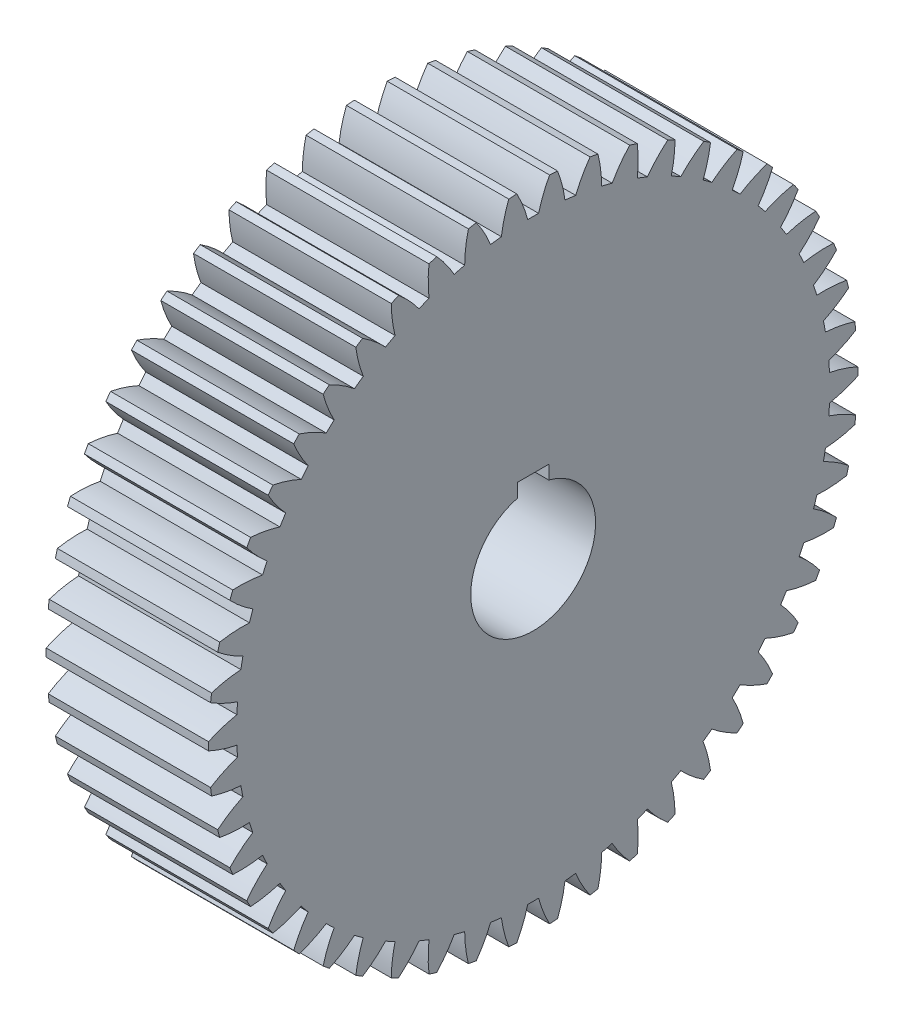
SolidWorks part; units mm, degrees
ref_plane "Plane1" through (0, 0, 0) normal (0, 0, 1) x (1, 0, 0)
ref_plane "Plane2" through (0, 0, 0) normal (0, 1, 0) x (1, 0, 0)
ref_plane "Plane3" through (0, 0, 0) normal (1, 0, 0) x (0, 0, -1)
sketch "HoldingSke" plane through (0, 0, 0) normal (0, 1, 0) x (1, 0, 0)
  line L0 (0, 0) -> (130.6144, -155.6602)
  line L1 (-15, 0) -> (100, 0) construction
  line L2 (0, 0) -> (-2.1039, 2.3779)
  line L3 (0, 0) -> (-11.863, 4.5341)
  line L4 (0, 0) -> (5.5511, 6.6156)
  line L5 (0, 0) -> (-47.5972, -17.7524)
  line L6 (0, 0) -> (-34.2154, -23.0853)
  line L7 (-2.1039, 2.3779) -> (8.8308, 51.9871)
  line L8 (-76.2, 54.61) -> (-41.4782, 54.61)
  line L9 (-71.009, 38.7566) -> (-53.1078, 45.2721)
  line L10 (-76.2, 71.12) -> (104.1128, 71.12)
  line L11 (0, 0) -> (-41.275, 0)
  line L12 (-76.2, 101.6) -> (-76.0857, 101.6)
  line L13 (24.9733, 27.94) -> (52.9518, 28.4284)
  line L14 (24.9733, 27.94) -> (24.9746, 27.94)
  line L15 (24.9733, 27.94) -> (100.4006, 29.5858)
  circle A0 centre (0, 0) radius 15.875
  circle A1 centre (0, 0) radius 38.1
  circle A2 centre (0, 0) radius 38.1
  circle A3 centre (0, 0) radius 15.875
  dimension "MHD" = 76.2
  dimension "Hub_dia" = 76.2
  dimension "Bore" = 31.75
  dimension "MBD" = 31.75
  dimension "Num_teeth" = 50
  dimension "Pitch" = 203.2
  dimension "Overall_len" = 50.8
  dimension "Show_teeth" = 50
  dimension "Thickness" = 41.275
  dimension "OAL" = 50.8001
  dimension "T_dim" = 34.7218
  dimension "Ap" = 20
  dimension "H" = 19.05
  dimension "Pitch_radius" = 180.3128
  dimension "Width" = 41.275
  dimension "Backlash" = 0.1143
  dimension "Addendum_fac" = 1
  dimension "Dedendum_fac" = 1.25
  dimension "Clearance_fac" = 0.25
  dimension "Dedendum_add" = 0.0013
sketch "BasProSke" plane through (0, 0, 0) normal (0, 1, 0) x (1, 0, 0)
  line L0 (-10, 0) -> (60, 0) construction
  line L1 (0, 0) -> (0, 82.55)
  line L2 (0, 0) -> (41.275, 0)
  line L3 (41.275, 0) -> (41.275, 82.55)
  line L4 (41.275, 82.55) -> (0, 82.55)
  dimension "Thickness" = 41.275
  dimension "Diameter" = 165.1
revolve "Base-Revolve" add sketch "BasProSke" angle 360 about L0
sketch "TooCutSke" plane through (0, 0, 0) normal (1, 0, 0) x (0, 0, -1)
  line L1 (0, 0) -> (0, 107) construction
  line L2 (0, 0) -> (-2.6932, 79.3293) construction
  line L3 (0, 0) -> (-9.9638, 158.3706) construction
  line L4 (-2.6932, 79.3293) -> (-4.9819, 79.1853) construction
  arc A0 (1.3795, 75.3924) -> (-1.3795, 75.3924) centre (0, 0) ccw
  arc A1 (4.1801, 82.4695) -> (-4.1801, 82.4695) centre (0, 0) ccw
  circle A2 centre (0, 0) radius 79.375 construction
  circle A3 centre (0, 0) radius 74.5881 construction
  arc A4 (-1.3795, 75.3924) -> (-4.1801, 82.4695) centre (-32.0894, 67.3324) ccw
  arc A5 (4.1801, 82.4695) -> (1.3795, 75.3924) centre (32.0894, 67.3324) ccw
  dimension "Root_dia" = 150.81
  dimension "Overcut_dia" = 165.1508
  dimension "Pitch_dia" = 158.75
  dimension "Base_dia" = 149.1762
  dimension "Flank_rad" = 31.75
  dimension "Half_ang" = 3.6
  dimension "Half_CT" = 2.2932
extrude "ToothCut" cut sketch "TooCutSke" along normal through all
fillet "Breaks" [suppressed] radius 0.0635
fillet "RootFillets" [suppressed] radius 0.795
pattern_circular "TeethCuts" count 50 every 7.2 about axis through (-10, 0, 0) along (1, 0, 0) of "ToothCut", "RootFillets", "Breaks"
sketch "HubNeaOneSke" plane through (0, 0, 0) normal (-1, 0, 0) x (0, 0, 1)
  circle A0 centre (0, 0) radius 38.1
  dimension "Diameter" = 76.2
extrude "HubNearOne" [suppressed] add sketch "HubNeaOneSke" along normal blind 9.5251
sketch "HubNeaBotSke" plane through (0, 0, 0) normal (-1, 0, 0) x (0, 0, 1)
  circle A0 centre (0, 0) radius 38.1
  dimension "Diameter" = 76.2
extrude "HubNearBoth" [suppressed] add sketch "HubNeaBotSke" along normal blind 4.7625
ref_plane "FarPln" through (41.275, 0, 0) normal (1, 0, 0) x (0, 0, -1)
sketch "HubFarSke" plane through (41.275, 0, 0) normal (1, 0, 0) x (0, 0, -1)
  circle A0 centre (0, 0) radius 38.1
  dimension "Diameter" = 76.2
extrude "HubFar" [suppressed] add sketch "HubFarSke" along normal blind 4.7625
sketch "BorSke" plane through (0, 0, 0) normal (1, 0, 0) x (0, 0, -1)
  circle A0 centre (0, 0) radius 15.875
  dimension "Diameter" = 31.75
extrude "Bore" cut sketch "BorSke" along normal mid plane 101.6001
sketch "KeySke" plane through (0, 0, 0) normal (1, 0, 0) x (0, 0, -1)
  line L0 (-3.9624, 0) -> (-3.9624, 18.8468)
  line L1 (-3.9624, 18.8468) -> (3.9624, 18.8468)
  line L2 (3.9624, 18.8468) -> (3.9624, 0)
  line L3 (0, 0) -> (0, 34) construction
  line L4 (-3.9624, 0) -> (3.9624, 0)
  dimension "Offset" = 18.8468
  dimension "Width" = 7.9248
extrude "Keyway" cut sketch "KeySke" along normal mid plane 101.6001
pattern_circular "Keyway2" [suppressed] count 2 every 90 about axis through (-10, 0, 0) along (1, 0, 0)
equation "' \"Pitch@HoldingSke\" = 4"
equation "' \"Num_teeth@HoldingSke\" = 12"
equation "' \"Ap@HoldingSke\" =  20"
equation "' \"Ap@HoldingSke\" = 20"
equation "' \"Width@HoldingSke\" = 0.5"
equation "' \"Hub_dia@HoldingSke\"= 1"
equation "' \"Hub_dia@HoldingSke\" = 1"
equation "' \"Overall_len@HoldingSke\" = 1.0"
equation "' \"Bore@HoldingSke\" = 0.75"
equation "' \"T_dim@HoldingSke\" = 0.85"
equation "' \"Width@KeySke\" = 0.25"
equation "' \"Show_teeth@HoldingSke\" = 13"
equation "' \"Backlash@HoldingSke\" = 0.009"
equation "' \"Addendum_fac@HoldingSke\" = 1.0"
equation "' \"Dedendum_fac@HoldingSke\" = 1.25"
equation "' \"Dedendum_add@HoldingSke\" = 0.00005"
equation "' \"Clearance_fac@HoldingSke\" = 0.25"
equation "' \"Pitch@HoldingSke\" = 0.5"
equation "' \"Num_teeth@HoldingSke\" = 23"
equation "' \"Show_teeth@HoldingSke\" = 23"
equation "' \"Backlash@HoldingSke\" = 0.0375"
equation "\"Overcut_dia@TooCutSke\" = (\"Num_teeth@HoldingSke\" + 2 * \"Addendum_fac@HoldingSke\") / \"Pitch@HoldingSke\" + 0.002"
equation "\"Pitch_dia@TooCutSke\" = \"Num_teeth@HoldingSke\" / \"Pitch@HoldingSke\""
equation "\"Base_dia@TooCutSke\" = \"Num_teeth@HoldingSke\" / \"Pitch@HoldingSke\" * cos((\"Ap@HoldingSke\"  * 3.14159265 / 180))"
equation "\"Root_dia@TooCutSke\" = (\"Num_teeth@HoldingSke\" + 2) / \"Pitch@HoldingSke\" - 2 * (\"Addendum_fac@HoldingSke\" + \"Dedendum_fac@HoldingSke\") / \"Pitch@HoldingSke\" - \"Dedendum_add@HoldingSke\" * 2"
equation "\"Half_ang@TooCutSke\" = 180 / \"Num_teeth@HoldingSke\""
equation "\"Half_CT@TooCutSke\" = \"Num_teeth@HoldingSke\" / \"Pitch@HoldingSke\" * sin((3.14159265 / 2 / \"Num_teeth@HoldingSke\")) / 2 - 7 * \"Backlash@HoldingSke\" / 4"
equation "\"Flank_rad@TooCutSke\" = \"Num_teeth@HoldingSke\" / \"Pitch@HoldingSke\" / 5"
equation "\"Radius@RootFillets\" = \"Clearance_fac@HoldingSke\" / \"Pitch@HoldingSke\" + \"Dedendum_add@HoldingSke\""
equation "\"Break_rad@Breaks\" = 0.02 / \"Pitch@HoldingSke\""
equation "\"Thickness@HoldingSke\" = \"Width@HoldingSke\""
equation "\"OAL@HoldingSke\" = \"Thickness@HoldingSke\""
equation "\"MHD@HoldingSke\" = (\"Num_teeth@HoldingSke\" + 2) / \"Pitch@HoldingSke\" - 2 * (\"Addendum_fac@HoldingSke\" + \"Dedendum_fac@HoldingSke\")  / \"Pitch@HoldingSke\" - \"Dedendum_add@HoldingSke\" * 2"
equation "\"MBD@HoldingSke\" = (\"Num_teeth@HoldingSke\" + 2) / \"Pitch@HoldingSke\" - 2 * (\"Addendum_fac@HoldingSke\" + \"Dedendum_fac@HoldingSke\")  / \"Pitch@HoldingSke\" - \"Dedendum_add@HoldingSke\" * 2 - 0.002"
equation "\"MHD@HoldingSke\" = ((sgn( \"MHD@HoldingSke\" - \"Hub_dia@HoldingSke\" )-1)*( \"MHD@HoldingSke\" - \"Hub_dia@HoldingSke\" ))/-2+ \"Hub_dia@HoldingSke\""
equation "\"MBD@HoldingSke\" = ((sgn( \"MBD@HoldingSke\" - \"Bore@HoldingSke\" )-1)*( \"MBD@HoldingSke\" - \"Bore@HoldingSke\" ))/-2+ \"Bore@HoldingSke\""
equation "\"OAL@HoldingSke\" = ((sgn( \"OAL@HoldingSke\" - \"Overall_len@HoldingSke\" )+1)*( \"OAL@HoldingSke\" - \"Overall_len@HoldingSke\" ))/2 + \"Overall_len@HoldingSke\" + 0.000002"
equation "\"Num_teeth@TeethCuts\" = int( \"Show_teeth@HoldingSke\" ) + 1"
equation "\"Num_teeth@TeethCuts\" = ((sgn( \"Num_teeth@TeethCuts\" - \"Num_teeth@HoldingSke\" )-1)*( \"Num_teeth@TeethCuts\" - \"Num_teeth@HoldingSke\" ))/-2+ \"Num_teeth@HoldingSke\""
equation "\"Num_teeth@TeethCuts\" = ((sgn( \"Num_teeth@TeethCuts\" - 2.0)+1)*( \"Num_teeth@TeethCuts\" - 2.0))/2 +2.0"
equation "\"Angle@TeethCuts\" = 360.0 / \"Num_teeth@HoldingSke\""
equation "\"Diameter@BasProSke\" = (\"Num_teeth@HoldingSke\" + 2 * \"Addendum_fac@HoldingSke\") / \"Pitch@HoldingSke\""
equation "\"Thickness@BasProSke\"  = \"Thickness@HoldingSke\""
equation "' \"Fillet_rad@BasProSke\" =  \"Thickness@HoldingSke\" * 0.05"
equation "' \"Fillet_rad@BasProSke\" = \"Thickness@HoldingSke\" * 0.05"
equation "\"MHD@HoldingSke\" = ((sgn( \"MHD@HoldingSke\" - \"Root_dia@TooCutSke\" )-1)*( \"MHD@HoldingSke\" - \"Root_dia@TooCutSke\" ))/-2+ \"Root_dia@TooCutSke\""
equation "\"Diameter@HubNeaOneSke\" = \"MHD@HoldingSke\""
equation "\"Length@HubNearOne\" = \"OAL@HoldingSke\" - \"Thickness@BasProSke\""
equation "\"Diameter@HubNeaBotSke\" = \"MHD@HoldingSke\""
equation "\"Length@HubNearBoth\" = ( \"OAL@HoldingSke\" - \"Thickness@BasProSke\" ) / 2.0"
equation "\"Thickness@FarPln\" = \"Thickness@BasProSke\""
equation "\"Diameter@HubFarSke\" = \"MHD@HoldingSke\""
equation "\"Length@HubFar\" = ( \"OAL@HoldingSke\" - \"Thickness@BasProSke\" ) / 2.0"
equation "\"Diameter@BorSke\" = \"MBD@HoldingSke\""
equation "\"D1@Bore\" = \"OAL@HoldingSke\" * 2.0"
equation "\"D1@Keyway\" = \"OAL@HoldingSke\" * 2.0"
equation "\"Offset@KeySke\" = \"T_dim@HoldingSke\" - \"MBD@HoldingSke\" / 2.0"
